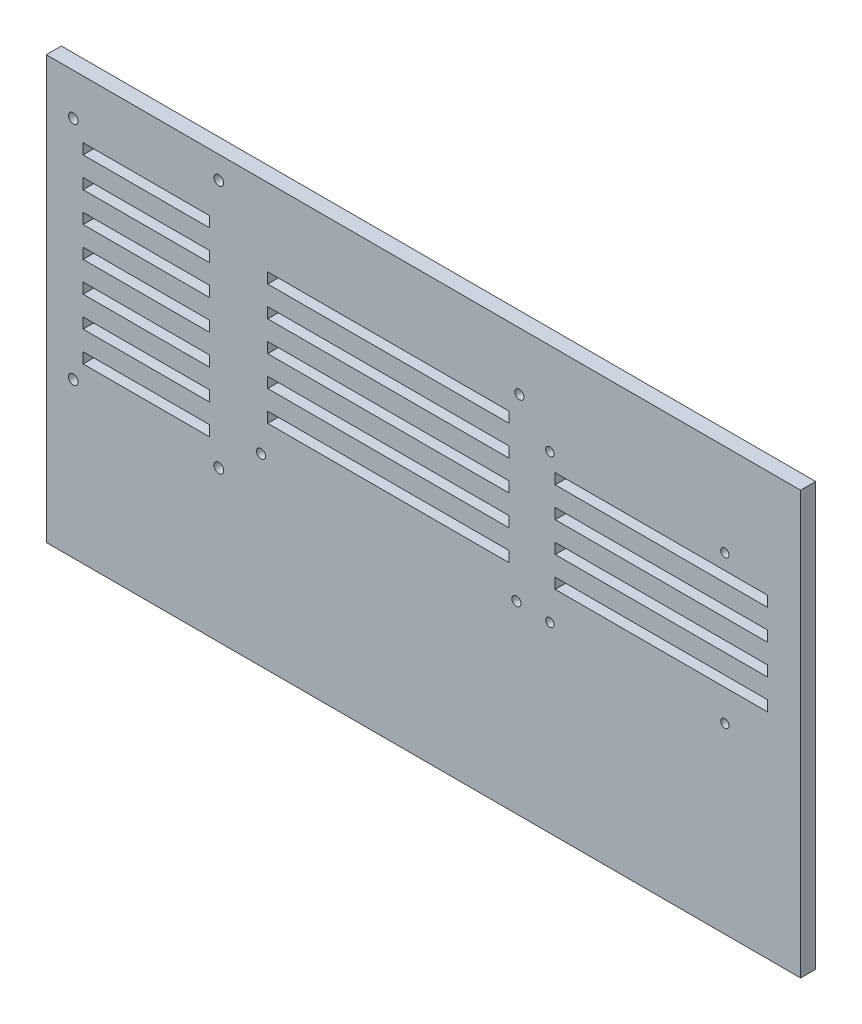
SolidWorks part; units mm, degrees
ref_plane "Alzado" through (0, 0, 0) normal (0, 0, 1) x (1, 0, 0)
ref_plane "Planta" through (0, 0, 0) normal (0, 1, 0) x (1, 0, 0)
ref_plane "Vista lateral" through (0, 0, 0) normal (1, 0, 0) x (0, 0, -1)
sketch "Croquis1" plane through (0, 0, 0) normal (0, 0, 1) x (1, 0, 0)
  line L0 (-110.6453, 86.3351) -> (139.3547, 86.3351)
  line L1 (-110.6453, 86.3351) -> (-110.6453, -53.6649)
  line L2 (-110.6453, -53.6649) -> (139.3547, -53.6649)
  line L3 (139.3547, 86.3351) -> (139.3547, -53.6649)
  line L4 (-101.7066, 72.5351) -> (-101.7066, -2.3949) construction
  line L5 (-53.4466, 78.8851) -> (-53.4466, -3.6649) construction
  line L6 (-101.7066, 72.5351) -> (-53.4466, 72.5351) construction
  line L7 (-53.4466, -3.6649) -> (-100.7334, -3.6649) construction
  line L8 (-98.4314, 57.1917) -> (-98.4314, 53.6917)
  line L9 (-98.4314, 67.1917) -> (-56.5715, 67.1917)
  line L10 (-98.4314, 67.1917) -> (-98.4314, 63.6917)
  line L11 (-98.4314, 63.6917) -> (-56.5715, 63.6917)
  line L12 (-56.5715, 67.1917) -> (-56.5715, 63.6917)
  line L13 (-98.4314, 57.1917) -> (-56.5715, 57.1917)
  line L14 (-56.5715, 57.1917) -> (-56.5715, 53.6917)
  line L15 (-98.4314, 53.6917) -> (-56.5715, 53.6917)
  line L16 (-98.4314, 47.1917) -> (-98.4314, 43.6917)
  line L17 (-98.4314, 47.1917) -> (-56.5715, 47.1917)
  line L18 (-56.5715, 47.1917) -> (-56.5715, 43.6917)
  line L19 (-98.4314, 43.6917) -> (-56.5715, 43.6917)
  line L20 (-98.4314, 37.1917) -> (-98.4314, 33.6917)
  line L21 (-98.4314, 37.1917) -> (-56.5715, 37.1917)
  line L22 (-56.5715, 37.1917) -> (-56.5715, 33.6917)
  line L23 (-98.4314, 33.6917) -> (-56.5715, 33.6917)
  line L24 (-98.4314, 27.1917) -> (-98.4314, 23.6917)
  line L25 (-98.4314, 27.1917) -> (-56.5715, 27.1917)
  line L26 (-56.5715, 27.1917) -> (-56.5715, 23.6917)
  line L27 (-98.4314, 23.6917) -> (-56.5715, 23.6917)
  line L28 (-98.4314, 17.1917) -> (-98.4314, 13.6917)
  line L29 (-98.4314, 17.1917) -> (-56.5715, 17.1917)
  line L30 (-56.5715, 17.1917) -> (-56.5715, 13.6917)
  line L31 (-98.4314, 13.6917) -> (-56.5715, 13.6917)
  line L32 (-98.4314, 7.1917) -> (-98.4314, 3.6917)
  line L33 (-98.4314, 7.1917) -> (-56.5715, 7.1917)
  line L34 (-56.5715, 7.1917) -> (-56.5715, 3.6917)
  line L35 (-98.4314, 3.6917) -> (-56.5715, 3.6917)
  line L36 (-37.2516, 50.7144) -> (-37.2516, 47.2144)
  line L37 (-37.2516, 60.7144) -> (42.7116, 60.7144)
  line L38 (-37.2516, 60.7144) -> (-37.2516, 57.2144)
  line L39 (-37.2516, 57.2144) -> (42.7116, 57.2144)
  line L40 (42.7116, 60.7144) -> (42.7116, 57.2144)
  line L41 (-37.2516, 50.7144) -> (42.7116, 50.7144)
  line L42 (42.7116, 50.7144) -> (42.7116, 47.2144)
  line L43 (-37.2516, 47.2144) -> (42.7116, 47.2144)
  line L44 (-37.2516, 40.7144) -> (-37.2516, 37.2144)
  line L45 (-37.2516, 40.7144) -> (42.7116, 40.7144)
  line L46 (42.7116, 40.7144) -> (42.7116, 37.2144)
  line L47 (-37.2516, 37.2144) -> (42.7116, 37.2144)
  line L48 (-37.2516, 30.7144) -> (-37.2516, 27.2144)
  line L49 (-37.2516, 30.7144) -> (42.7116, 30.7144)
  line L50 (42.7116, 30.7144) -> (42.7116, 27.2144)
  line L51 (-37.2516, 27.2144) -> (42.7116, 27.2144)
  line L52 (-37.2516, 20.7144) -> (-37.2516, 17.2144)
  line L53 (-37.2516, 20.7144) -> (42.7116, 20.7144)
  line L54 (42.7116, 20.7144) -> (42.7116, 17.2144)
  line L55 (-37.2516, 17.2144) -> (42.7116, 17.2144)
  line L56 (58.0228, 40.7144) -> (58.0228, 37.2144)
  line L57 (58.0228, 50.7144) -> (128.3695, 50.7144)
  line L58 (58.0228, 50.7144) -> (58.0228, 47.2144)
  line L59 (58.0228, 47.2144) -> (128.3695, 47.2144)
  line L60 (128.3695, 50.7144) -> (128.3695, 47.2144)
  line L61 (58.0228, 40.7144) -> (128.3695, 40.7144)
  line L62 (128.3695, 40.7144) -> (128.3695, 37.2144)
  line L63 (58.0228, 37.2144) -> (128.3695, 37.2144)
  line L64 (58.0228, 30.7144) -> (58.0228, 27.2144)
  line L65 (58.0228, 30.7144) -> (128.3695, 30.7144)
  line L66 (128.3695, 30.7144) -> (128.3695, 27.2144)
  line L67 (58.0228, 27.2144) -> (128.3695, 27.2144)
  line L68 (58.0228, 20.7144) -> (58.0228, 17.2144)
  line L69 (58.0228, 20.7144) -> (128.3695, 20.7144)
  line L70 (128.3695, 20.7144) -> (128.3695, 17.2144)
  line L71 (58.0228, 17.2144) -> (128.3695, 17.2144)
  circle A0 centre (-101.7066, -2.3949) radius 1.6
  circle A1 centre (-53.4466, -3.6649) radius 1.6
  circle A2 centre (114.2472, 6.8486) radius 1.375
  circle A3 centre (114.2472, 55.8486) radius 1.375
  circle A4 centre (56.2472, 6.8486) radius 1.375
  circle A5 centre (56.2472, 55.8486) radius 1.375
  circle A6 centre (46.1592, 67.2144) radius 1.5
  circle A7 centre (45.1592, 7.4144) radius 1.5
  circle A8 centre (-39.4608, 7.4144) radius 1.5
  circle A9 centre (-101.7066, 72.5351) radius 1.6
  circle A10 centre (-53.4466, 78.8851) radius 1.6
  dimension "D1" = 3.2
  dimension "D2" = 2.75
  dimension "D3" = 3
  dimension "D4" = 45.1592
  dimension "D5" = 46.1592
  dimension "D6" = 56.2472
  dimension "D7" = 114.2472
  dimension "D8" = 139.3547
  dimension "D9" = 39.4608
  dimension "D10" = 53.4466
  dimension "D11" = 101.7066
  dimension "D12" = 110.6453
  dimension "D13" = 50
  dimension "D14" = 1.27
  dimension "D15" = 55.8486
  dimension "D16" = 67.2144
  dimension "D17" = 74.93
  dimension "D18" = 82.55
  dimension "D19" = 86.3351
  dimension "D20" = 7
  dimension "D21" = 5
  dimension "D22" = 53.6649
  dimension "D24" = 3.5
  dimension "D25" = 3.5
  dimension "D26" = 3.5
  dimension "D23" = 4
extrude "Saliente-Extruir1" add sketch "Croquis1" along normal blind 5
